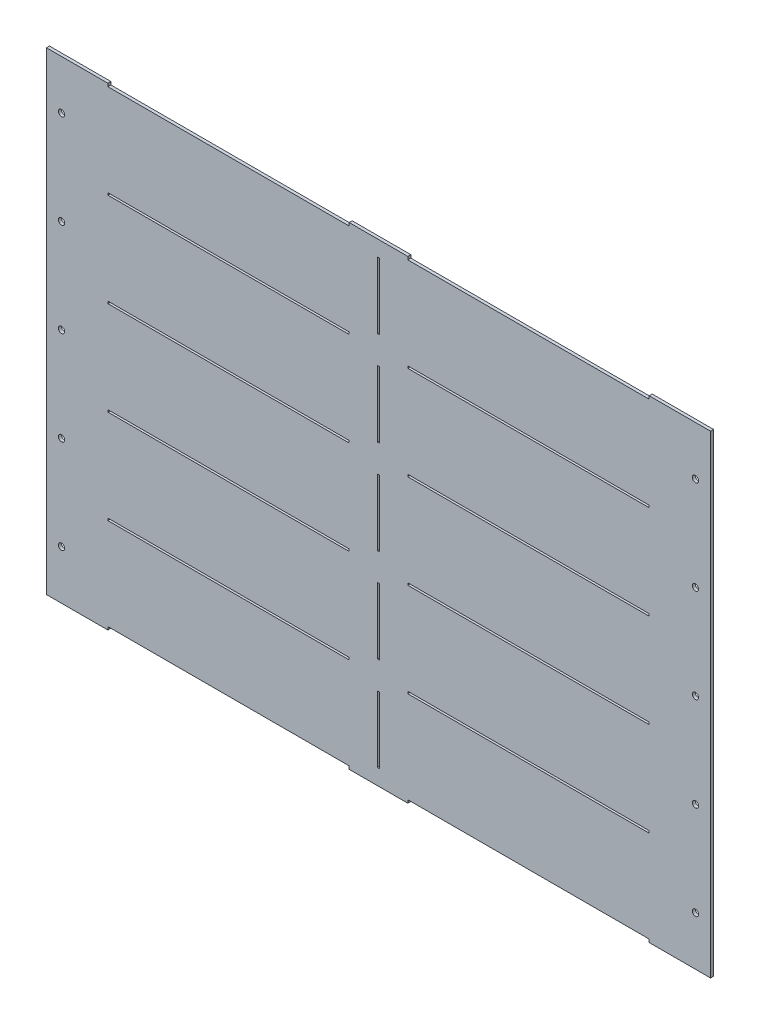
SolidWorks part; units mm, degrees
material "6061-T6 (SS)"
ref_plane "X-Y Datum" through (0, 0, 0) normal (0, 0, 1) x (1, 0, 0)
ref_plane "X-Z Datum" through (0, 0, 0) normal (0, 1, 0) x (1, 0, 0)
ref_plane "Y-Z Datum" through (0, 0, 0) normal (1, 0, 0) x (0, 0, -1)
sketch "Master Sketch" plane through (0, 0, 0) normal (0, 0, 1) x (1, 0, 0)
  line L0 (1.143, 50.5714) -> (314.5028, 50.5714) construction
  line L1 (-317.6778, 249.174) -> (317.6778, 249.174)
  line L2 (-317.6778, 249.174) -> (-317.6778, -249.174)
  line L3 (-317.6778, -249.174) -> (317.6778, -249.174)
  line L4 (317.6778, 249.174) -> (317.6778, -249.174)
  line L5 (-317.6778, 249.174) -> (317.6778, -249.174) construction
  line L6 (-317.6778, -249.174) -> (317.6778, 249.174) construction
  line L7 (-1.143, 249.174) -> (1.143, 249.174) construction
  line L8 (-1.143, 249.174) -> (-1.143, -249.174) construction
  line L9 (-1.143, -249.174) -> (1.143, -249.174) construction
  line L10 (1.143, 249.174) -> (1.143, -249.174) construction
  line L11 (-1.143, 249.174) -> (1.143, -249.174) construction
  line L12 (-1.143, -249.174) -> (1.143, 249.174) construction
  line L13 (1.143, 245.999) -> (314.5028, 245.999) construction
  line L14 (1.143, 245.999) -> (1.143, 149.4282) construction
  line L15 (1.143, 149.4282) -> (314.5028, 149.4282) construction
  line L16 (314.5028, 245.999) -> (314.5028, 149.4282) construction
  line L17 (1.143, 245.999) -> (314.5028, 149.4282) construction
  line L18 (1.143, 149.4282) -> (314.5028, 245.999) construction
  line L19 (1.143, 147.1422) -> (314.5028, 147.1422) construction
  line L20 (314.5028, 147.1422) -> (314.5028, 50.5714) construction
  line L21 (1.143, 147.1422) -> (1.143, 50.5714) construction
  line L22 (1.143, -48.2854) -> (314.5028, -48.2854) construction
  line L23 (1.143, 48.2854) -> (314.5028, 48.2854) construction
  line L24 (314.5028, 48.2854) -> (314.5028, -48.2854) construction
  line L25 (1.143, 48.2854) -> (1.143, -48.2854) construction
  line L26 (1.143, -147.1422) -> (314.5028, -147.1422) construction
  line L27 (1.143, -50.5714) -> (314.5028, -50.5714) construction
  line L28 (314.5028, -50.5714) -> (314.5028, -147.1422) construction
  line L29 (1.143, -50.5714) -> (1.143, -147.1422) construction
  line L30 (1.143, -245.999) -> (314.5028, -245.999) construction
  line L31 (1.143, -149.4282) -> (314.5028, -149.4282) construction
  line L32 (314.5028, -149.4282) -> (314.5028, -245.999) construction
  line L33 (1.143, -149.4282) -> (1.143, -245.999) construction
  line L34 (0, 249.174) -> (0, -249.174) construction
  line L35 (-1.143, -149.4282) -> (-1.143, -245.999) construction
  line L36 (-314.5028, -149.4282) -> (-314.5028, -245.999) construction
  line L37 (-1.143, -149.4282) -> (-314.5028, -149.4282) construction
  line L38 (-1.143, -245.999) -> (-314.5028, -245.999) construction
  line L39 (-1.143, -50.5714) -> (-1.143, -147.1422) construction
  line L40 (-314.5028, -50.5714) -> (-314.5028, -147.1422) construction
  line L41 (-1.143, -50.5714) -> (-314.5028, -50.5714) construction
  line L42 (-1.143, -147.1422) -> (-314.5028, -147.1422) construction
  line L43 (-1.143, 48.2854) -> (-1.143, -48.2854) construction
  line L44 (-314.5028, 48.2854) -> (-314.5028, -48.2854) construction
  line L45 (-1.143, 48.2854) -> (-314.5028, 48.2854) construction
  line L46 (-1.143, -48.2854) -> (-314.5028, -48.2854) construction
  line L47 (-1.143, 147.1422) -> (-1.143, 50.5714) construction
  line L48 (-314.5028, 147.1422) -> (-314.5028, 50.5714) construction
  line L49 (-1.143, 147.1422) -> (-314.5028, 147.1422) construction
  line L50 (-1.143, 149.4282) -> (-314.5028, 245.999) construction
  line L51 (-1.143, 245.999) -> (-314.5028, 149.4282) construction
  line L52 (-314.5028, 245.999) -> (-314.5028, 149.4282) construction
  line L53 (-1.143, 149.4282) -> (-314.5028, 149.4282) construction
  line L54 (-1.143, 245.999) -> (-1.143, 149.4282) construction
  line L55 (-1.143, 245.999) -> (-314.5028, 245.999) construction
  line L56 (-1.143, 249.174) -> (-1.143, -249.174) construction
  line L57 (-1.143, 50.5714) -> (-314.5028, 50.5714) construction
  line L59 (2.413, -152.8699) -> (313.2328, -152.8699) construction
  line L60 (2.413, -152.8699) -> (2.413, -242.5573) construction
  line L61 (2.413, -242.5573) -> (313.2328, -242.5573) construction
  line L62 (313.2328, -152.8699) -> (313.2328, -242.5573) construction
  line L63 (2.413, -152.8699) -> (313.2328, -242.5573) construction
  line L64 (2.413, -242.5573) -> (313.2328, -152.8699) construction
  point P0 (0, 0)
  point P6 (0, 0)
  point P11 (157.8229, 197.7136)
  point P54 (-157.8229, 197.7136)
  point P55 (157.8229, -197.7136)
  point P60 (157.8229, -149.4282)
  point P61 (314.5028, -197.7136)
  point P62 (-314.5028, 98.8568)
  point P63 (-314.5028, 0)
  dimension "D1" = 3.175
  dimension "D2" = 498.348
  dimension "D3" = 2.286
  dimension "D4" = 313.3598
  dimension "D5" = 96.5708
  dimension "D6" = 3.175
  dimension "D7" = 5
  dimension "D8" = 2.286
  dimension "D9" = 89.6874
  dimension "D10" = 310.8198
  dimension "D11" = 98.8568
  dimension "D12" = 635.3556
extrude "Boss-Extrude1" add sketch "Master Sketch" along normal blind 3.175
sketch "Sketch2" plane through (0, 0, 3.175) normal (0, 0, 1) x (1, 0, 0)
  line L0 (0, 317.2302) -> (0, -317.2302) construction
  line L1 (317.6778, 249.174) -> (-317.6778, 249.174) construction
  line L2 (-317.6778, -249.174) -> (-349.4278, -249.174)
  line L3 (-317.6778, -249.174) -> (-317.6778, 249.174)
  line L4 (-317.6778, 249.174) -> (-349.4278, 249.174)
  line L5 (-349.4278, -249.174) -> (-349.4278, 249.174)
  line L6 (-333.5528, 249.174) -> (-333.5528, -249.174) construction
  line L7 (-380.7135, 0) -> (380.7135, 0) construction
  circle A1 centre (-333.5528, 0) radius 3 construction
  circle A2 centre (-333.5528, -98.806) radius 3 construction
  circle A3 centre (-333.5528, -197.612) radius 3 construction
  circle A4 centre (-333.5528, 197.612) radius 3 construction
  circle A5 centre (-333.5528, 98.806) radius 3 construction
  point P4 (0, 0)
  point P18 (0, 0)
  dimension "D2" = 6
  dimension "D1" = 31.75
  dimension "D4" = 98.806
  dimension "D5" = 98.806
  dimension "D3" = 3
extrude "Boss-Extrude2" add sketch "Sketch2" against normal blind 3.175
hole_wizard "M6 Clearance Hole1" positions "Sketch3" profile "Sketch4" hole size "M6" standard "ANSI Metric" end condition through all
sketch "Sketch3" plane through (0, 0, 3.175) normal (0, 0, 1) x (1, 0, 0)
  point P0 (-333.5528, -197.612)
  point P3 (-333.5528, -98.806)
  point P6 (-333.5528, 0)
  point P9 (-333.5528, 98.806)
  point P12 (-333.5528, 197.612)
sketch "Sketch4" plane through (-333.5528, -197.612, 3.175) normal (1, 0, 0) x (0, -1, 0)
  line L0 (0, 0) -> (0, 3.175)
  line L1 (0, 3.175) -> (3.3, 3.175)
  line L2 (3.3, 3.175) -> (3.3, 0)
  line L5 (3.3, 0) -> (0, 0)
  line L11 (0, -6.35) -> (0, 107.95) construction
  dimension "Thru Hole Dia." = 6.6
  dimension "Thru Hole Depth" = 3.175
mirror "Mirror1" about plane through (0, 0, 0) normal (1, 0, 0) of "Boss-Extrude2", "M6 Clearance Hole1"
sketch "Sketch5" plane through (0, 0, 3.175) normal (0, 0, 1) x (1, 0, 0)
  line L5 (-1.143, 232.6386) -> (1.143, 232.6386)
  line L6 (-1.143, 232.6386) -> (-1.143, 162.7886)
  line L7 (-1.143, 162.7886) -> (1.143, 162.7886)
  line L8 (1.143, 232.6386) -> (1.143, 162.7886)
  line L9 (-157.8229, 197.7136) -> (157.8229, 197.7136) construction
  line L10 (-1.143, 232.6386) -> (1.143, 162.7886) construction
  line L11 (-1.143, 162.7886) -> (1.143, 232.6386) construction
  point P0 (0, 0)
  point P1 (0, 197.7136)
  dimension "D1" = 2.286
  dimension "D2" = 69.85
extrude "Cut-Extrude1" cut sketch "Sketch5" against normal through all
pattern_linear "LPattern1" count 5 spacing 98.8568 along (0, -1, 0) of "Cut-Extrude1"
sketch "Sketch6" plane through (0, 0, 3.175) normal (0, 0, 1) x (1, 0, 0)
  line L0 (-157.8229, 245.999) -> (-157.8229, 249.174) construction
  line L1 (-1.143, 245.999) -> (-314.5028, 245.999) construction
  line L2 (-317.6778, 249.174) -> (317.6778, 249.174) construction
  line L3 (0, -274.0914) -> (0, 274.0914) construction
  line L4 (-284.8229, 249.174) -> (-30.8229, 249.174)
  line L5 (-284.8229, 249.174) -> (-284.8229, 245.999)
  line L6 (-284.8229, 245.999) -> (-30.8229, 245.999)
  line L7 (-30.8229, 249.174) -> (-30.8229, 245.999)
  line L8 (-284.8229, 249.174) -> (-30.8229, 245.999) construction
  line L9 (-284.8229, 245.999) -> (-30.8229, 249.174) construction
  line L10 (30.8229, 249.174) -> (30.8229, 245.999)
  line L11 (284.8229, 249.174) -> (30.8229, 249.174)
  line L12 (284.8229, 245.999) -> (30.8229, 245.999)
  line L13 (284.8229, 249.174) -> (284.8229, 245.999)
  point P6 (-157.8229, 247.5865)
  dimension "D1" = 3.175
  dimension "D2" = 254
extrude "Cut-Extrude2" cut sketch "Sketch6" against normal through all
mirror "Mirror3" about plane through (0, 0, 0) normal (0, 1, 0) of "Cut-Extrude2"
sketch "Sketch7" plane through (0, 0, 3.175) normal (0, 0, 1) x (1, 0, 0)
  line L0 (-157.8229, 149.4282) -> (-157.8229, 147.1422) construction
  line L1 (-1.143, 149.4282) -> (-314.5028, 149.4282) construction
  line L2 (-1.143, 147.1422) -> (-314.5028, 147.1422) construction
  line L3 (-157.8229, 50.5714) -> (-157.8229, 48.2854) construction
  line L4 (-284.8229, 149.4282) -> (-30.8229, 149.4282)
  line L5 (-284.8229, 149.4282) -> (-284.8229, 147.1422)
  line L6 (-284.8229, 147.1422) -> (-30.8229, 147.1422)
  line L7 (-30.8229, 149.4282) -> (-30.8229, 147.1422)
  line L8 (-284.8229, 149.4282) -> (-30.8229, 147.1422) construction
  line L9 (-284.8229, 147.1422) -> (-30.8229, 149.4282) construction
  line L10 (-1.143, 50.5714) -> (-314.5028, 50.5714) construction
  line L11 (-1.143, 48.2854) -> (-314.5028, 48.2854) construction
  point P6 (-157.8229, 148.2852)
  dimension "D1" = 2.286
  dimension "D2" = 254
extrude "Cut-Extrude3" cut sketch "Sketch7" against normal through all
pattern_linear "LPattern2" count 4 spacing 98.8568 along (0, -1, 0) of "Cut-Extrude3"
mirror "Mirror4" about plane through (0, 0, 0) normal (1, 0, 0) of "LPattern2", "Cut-Extrude3"
sketch "Sketch8" plane through (0, 0, 3.175) normal (0, 0, 1) x (1, 0, 0)
  line L0 (-314.5028, 98.8568) -> (-317.6778, 98.8568) construction
  line L1 (-317.6778, 249.174) -> (-317.6778, -249.174) construction
  line L2 (349.4456, 0) -> (-349.4456, 0) construction
  line L3 (-317.6778, 121.0818) -> (-314.5028, 121.0818)
  line L4 (-317.6778, 121.0818) -> (-317.6778, 76.6318)
  line L5 (-317.6778, 76.6318) -> (-314.5028, 76.6318)
  line L6 (-314.5028, 121.0818) -> (-314.5028, 76.6318)
  line L7 (-317.6778, 121.0818) -> (-314.5028, 76.6318) construction
  line L8 (-317.6778, 76.6318) -> (-314.5028, 121.0818) construction
  line L9 (-317.6778, -121.0818) -> (-314.5028, -121.0818)
  line L10 (-314.5028, -121.0818) -> (-314.5028, -76.6318)
  line L11 (-317.6778, -121.0818) -> (-317.6778, -76.6318)
  line L12 (-317.6778, -76.6318) -> (-314.5028, -76.6318)
  point P5 (-316.0903, 98.8568)
  dimension "D1" = 3.175
  dimension "D2" = 44.45
extrude "Cut-Extrude4" [suppressed] cut sketch "Sketch8" against normal through all
mirror "Mirror5" [suppressed] about plane through (0, 0, 0) normal (1, 0, 0)
